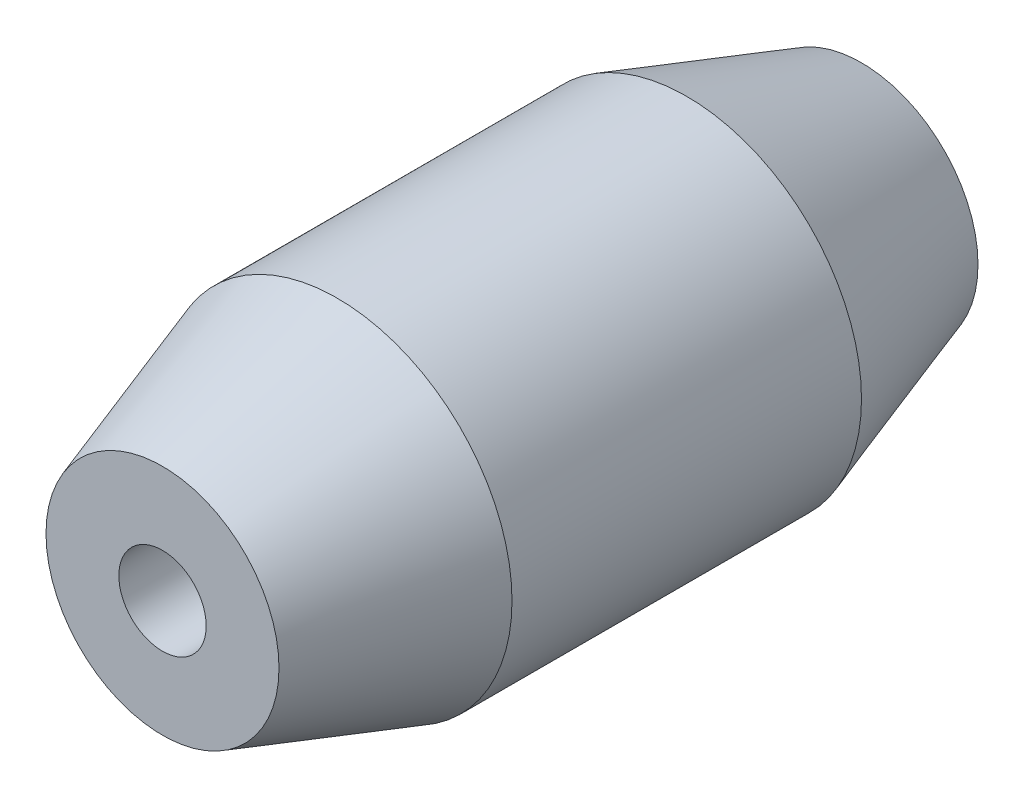
SolidWorks part; units mm, degrees
ref_plane "Plan de face" through (0, 0, 0) normal (0, 0, 1) x (1, 0, 0)
ref_plane "Plan de dessus" through (0, 0, 0) normal (0, 1, 0) x (1, 0, 0)
ref_plane "Plan de droite" through (0, 0, 0) normal (1, 0, 0) x (0, 0, -1)
sketch "Esquisse1" plane through (0, 0, 0) normal (0, 0, 1) x (1, 0, 0)
  circle A0 centre (0, 0) radius 3
  circle A1 centre (0, 0) radius 0.75
  dimension "D1" = 6
  dimension "D2" = 1.5
extrude "Boss.-Extru.1" add sketch "Esquisse1" along normal blind 12
chamfer "Chanfrein1" distance 3 distance2 1 1 edges at (3, 0, 12)
chamfer "Chanfrein2" distance 1 distance2 3 1 edges at (3, 0, 0)
